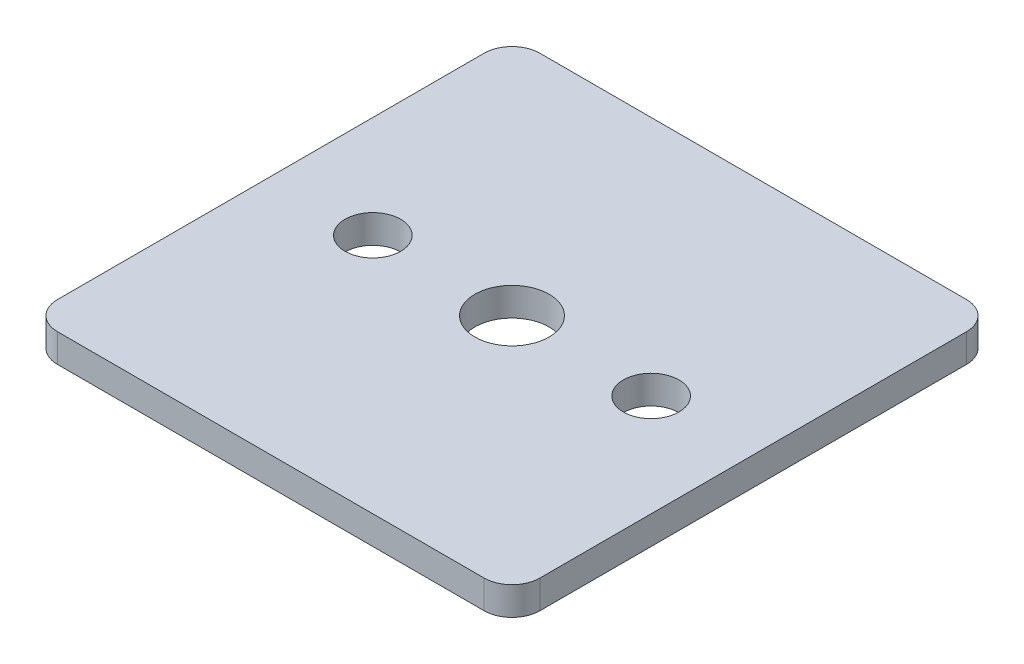
SolidWorks part; units mm, degrees
material "POM Acetal Copolymer"
ref_plane "Front Plane" through (0, 0, 0) normal (0, 0, 1) x (1, 0, 0)
ref_plane "Top Plane" through (0, 0, 0) normal (0, 1, 0) x (1, 0, 0)
ref_plane "Right Plane" through (0, 0, 0) normal (1, 0, 0) x (0, 0, -1)
sketch "Sketch2" plane through (0, 0, 0) normal (0, 1, 0) x (1, 0, 0)
  line L0 (-13, 13) -> (13, 13)
  line L1 (-1000, 0) -> (49000, 0) construction
  line L2 (0, -1000) -> (0, 49000) construction
  line L5 (13, 13) -> (13, -13)
  line L6 (13, -13) -> (-13, -13)
  line L7 (0, 0) -> (13, 13) construction
  line L8 (-13, -13) -> (-13, 13)
  line L9 (0, 0) -> (13, -13) construction
  line L10 (-13, 13) -> (0, 0) construction
  line L11 (-13, -13) -> (0, 0) construction
  circle A1 centre (7.5, 0) radius 1.5
  circle A2 centre (-7.5, 0) radius 1.5
  circle A5 centre (0, 0) radius 2
  dimension "D2" = 26
  dimension "D8" = 4
  dimension "D6" = 3
  dimension "D3" = 15
  dimension "D5" = 7.5
extrude "Boss-Extrude1" add sketch "Sketch2" along normal blind 1.5294
fillet "Fillet1" radius 1.5 4 edges at (13, 0.7647, 13) (13, 0.7647, -13) (-13, 0.7647, -13) (-13, 0.7647, 13)
equation "\"`2.5\"=3"
